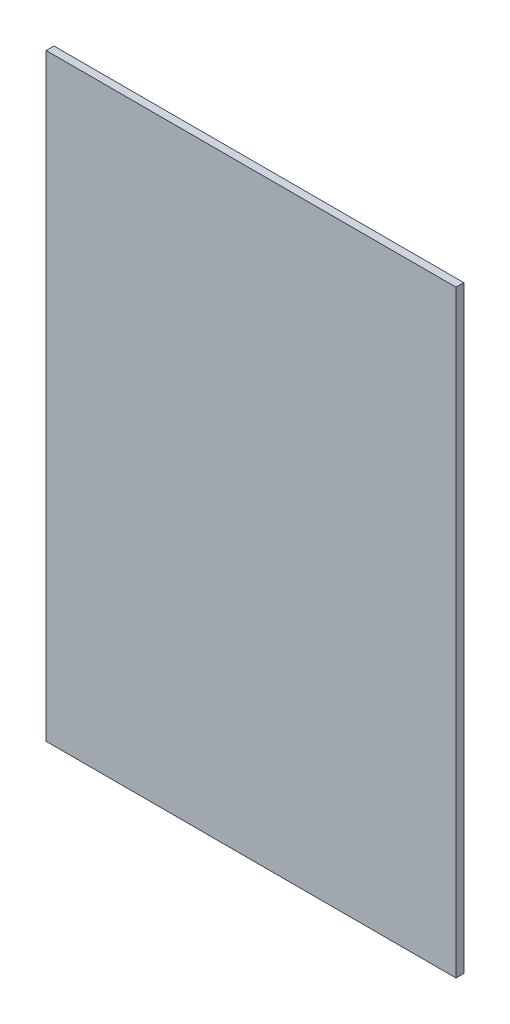
SolidWorks part; units mm, degrees
material "Acrylic (Medium-high impact)"
ref_plane "Front Plane" through (0, 0, 0) normal (0, 0, 1) x (1, 0, 0)
ref_plane "Top Plane" through (0, 0, 0) normal (0, 1, 0) x (1, 0, 0)
ref_plane "Right Plane" through (0, 0, 0) normal (1, 0, 0) x (0, 0, -1)
sketch "Sketch1" plane through (0, 0, 0) normal (0, 0, 1) x (1, 0, 0)
  line L1 (0, 0) -> (166.124, 0)
  line L2 (0, 0) -> (0, 242.52)
  line L3 (0, 242.52) -> (166.124, 242.52)
  line L4 (166.124, 0) -> (166.124, 242.52)
  dimension "D1" = 166.124
  dimension "D2" = 242.52
extrude "Boss-Extrude1" add sketch "Sketch1" along normal blind 3.175
